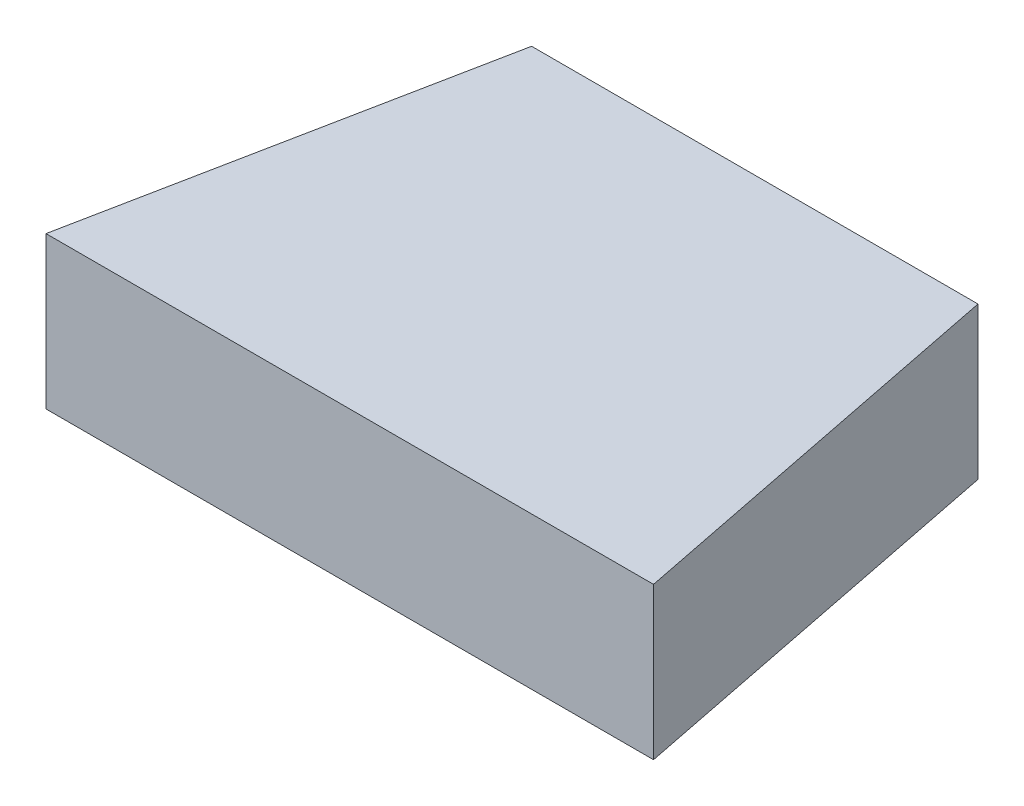
SolidWorks part; units mm, degrees
ref_plane "Front" through (0, 0, 0) normal (0, 0, 1) x (1, 0, 0)
ref_plane "Top" through (0, 0, 0) normal (0, 1, 0) x (1, 0, 0)
ref_plane "Right" through (0, 0, 0) normal (1, 0, 0) x (0, 0, -1)
sketch "Sketch1" plane through (0, 0, 0) normal (0, 1, 0) x (1, 0, 0)
  line L0 (140.7416, -27.9953) -> (140.7416, 27.9953) construction
  line L1 (191.5416, -38.1) -> (191.5416, 38.1) construction
  line L2 (191.5416, 38.1) -> (162.3812, 108.4996) construction
  line L3 (162.3812, 108.4996) -> (108.4996, 162.3812) construction
  line L4 (108.4996, 162.3812) -> (38.1, 191.5416) construction
  line L5 (38.1, 191.5416) -> (-38.1, 191.5416) construction
  line L6 (-38.1, 191.5416) -> (-108.4996, 162.3812) construction
  line L7 (-108.4996, 162.3812) -> (-162.3812, 108.4996) construction
  line L8 (-162.3812, 108.4996) -> (-191.5416, 38.1) construction
  line L9 (-191.5416, 38.1) -> (-191.5416, -38.1) construction
  line L10 (-191.5416, -38.1) -> (-162.3812, -108.4996) construction
  line L11 (-162.3812, -108.4996) -> (-108.4996, -162.3812) construction
  line L12 (-108.4996, -162.3812) -> (-38.1, -191.5416) construction
  line L13 (-38.1, -191.5416) -> (38.1, -191.5416)
  line L14 (38.1, -191.5416) -> (108.4996, -162.3812) construction
  line L15 (108.4996, -162.3812) -> (162.3812, -108.4996) construction
  line L16 (162.3812, -108.4996) -> (191.5416, -38.1) construction
  line L17 (140.7416, 27.9953) -> (119.315, 79.7237) construction
  line L18 (119.315, 79.7237) -> (79.7237, 119.315) construction
  line L19 (79.7237, 119.315) -> (27.9953, 140.7416) construction
  line L20 (27.9953, 140.7416) -> (-27.9953, 140.7416) construction
  line L21 (-27.9953, 140.7416) -> (-79.7237, 119.315) construction
  line L22 (-79.7237, 119.315) -> (-119.315, 79.7237) construction
  line L23 (-119.315, 79.7237) -> (-140.7416, 27.9953) construction
  line L24 (-140.7416, 27.9953) -> (-140.7416, -27.9953) construction
  line L25 (-140.7416, -27.9953) -> (-119.315, -79.7237) construction
  line L26 (-119.315, -79.7237) -> (-79.7237, -119.315) construction
  line L27 (-79.7237, -119.315) -> (-27.9953, -140.7416) construction
  line L28 (-27.9953, -140.7416) -> (27.9953, -140.7416)
  line L29 (27.9953, -140.7416) -> (79.7237, -119.315) construction
  line L30 (79.7237, -119.315) -> (119.315, -79.7237) construction
  line L31 (119.315, -79.7237) -> (140.7416, -27.9953) construction
  line L32 (0, 0) -> (-27.9953, -140.7416) construction
  line L33 (0, 0) -> (27.9953, -140.7416) construction
  line L34 (-27.9953, -140.7416) -> (-38.1, -191.5416)
  line L36 (27.9953, -140.7416) -> (38.1, -191.5416)
  circle A0 centre (0, 0) radius 191.5416 construction
  circle A1 centre (0, 0) radius 140.7416 construction
  dimension "D1" = 76.2
  dimension "D2" = 50.8
extrude "Boss-Extrude1" add sketch "Sketch1" along normal blind 19.05
